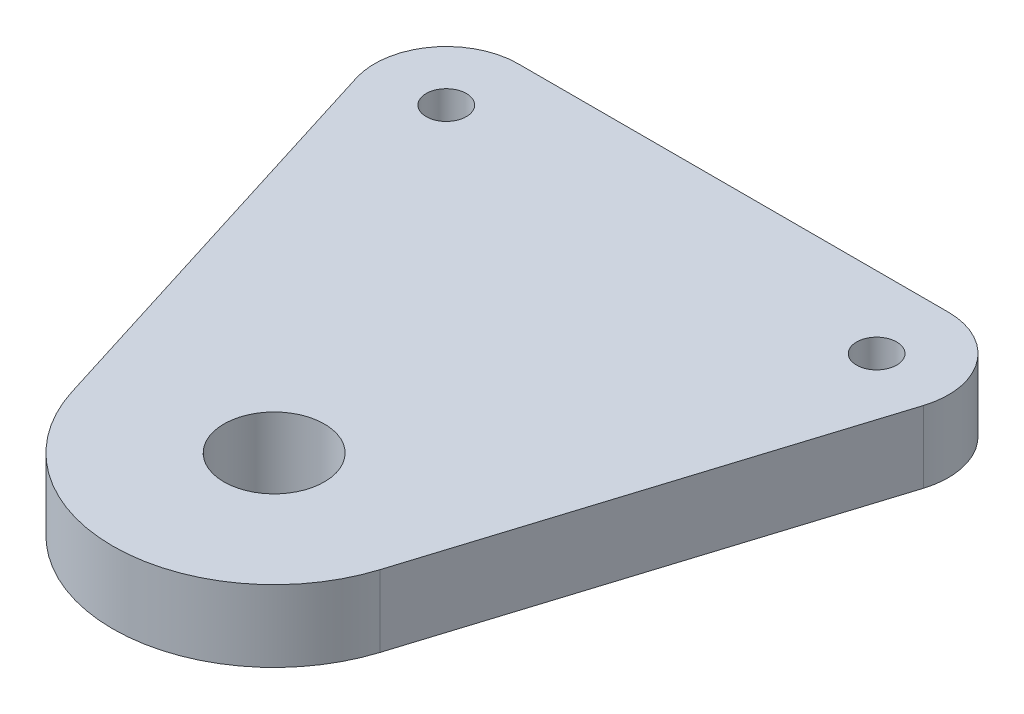
SolidWorks part; units mm, degrees
ref_plane "Front Plane" through (0, 0, 0) normal (0, 0, 1) x (1, 0, 0)
ref_plane "Top Plane" through (0, 0, 0) normal (0, 1, 0) x (1, 0, 0)
ref_plane "Right Plane" through (0, 0, 0) normal (1, 0, 0) x (0, 0, -1)
sketch "Sketch1" plane through (0, 0, 0) normal (0, 1, 0) x (1, 0, 0)
  line L0 (-15, 27) -> (15, 27) construction
  line L1 (-15, 32) -> (15, 32)
  line L2 (-15, 22) -> (15, 22) construction
  line L3 (-10.7364, -3.3605) -> (-19.7717, 25.5065)
  line L4 (19.7717, 25.5065) -> (10.7364, -3.3605)
  circle A0 centre (0, 0) radius 3.5
  arc A1 (-10.7364, -3.3605) -> (10.7364, -3.3605) centre (0, 0) ccw
  arc A2 (-15, 32) -> (-19.7717, 25.5065) centre (-15, 27) ccw
  arc A3 (19.7717, 25.5065) -> (15, 32) centre (15, 27) ccw
  arc A4 (-19.7717, 25.5065) -> (-15, 22) centre (-15, 27) ccw construction
  arc A5 (15, 22) -> (19.7717, 25.5065) centre (15, 27) ccw construction
  arc A6 (10.7364, -3.3605) -> (-10.7364, -3.3605) centre (0, 0) ccw construction
  circle A7 centre (-15, 27) radius 1.4
  circle A8 centre (15, 27) radius 1.4
  point P6 (0, 27)
  dimension "D1" = 7
  dimension "D2" = 22.5
  dimension "D4" = 5
  dimension "D6" = 2.8
  dimension "D3" = 30
  dimension "D5" = 32
extrude "Boss-Extrude1" add sketch "Sketch1" along normal blind 5
